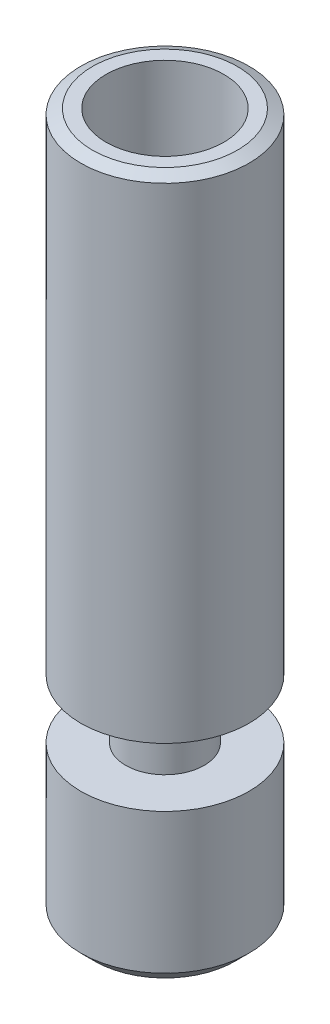
SolidWorks part; units mm, degrees
material "1060 Alloy"
ref_plane "Front Plane" through (0, 0, 0) normal (0, 0, 1) x (1, 0, 0)
ref_plane "Top Plane" through (0, 0, 0) normal (0, 1, 0) x (1, 0, 0)
ref_plane "Right Plane" through (0, 0, 0) normal (1, 0, 0) x (0, 0, -1)
ref_plane "Plane1" through (0, 0, 0) normal (0, 0, -1) x (-1, 0, 0)
sketch "Sketch1" plane through (0, 0, 0) normal (0, 0, -1) x (-1, 0, 0)
  line L0 (-2.5, -0.5) -> (-1, -0.5)
  line L1 (-1, -0.5) -> (-1, 15.3)
  line L2 (-1, 15.3) -> (-2.1, 16.4)
  line L3 (-2.1, 16.4) -> (-2.1, 24.5963)
  line L4 (-2.1, 24.5963) -> (-2.5868, 24.5963)
  line L5 (-3, 24.4) -> (-2.5868, 24.5963)
  line L6 (-3, 24.4) -> (-3, 16.9)
  line L8 (-3, 16.9) -> (-3, 7.1)
  line L9 (-3, 7.1) -> (-1.4, 7.1)
  line L10 (-1.4, 7.1) -> (-1.4, 5)
  line L11 (-1.4, 5) -> (-3, 5)
  line L12 (-3, 5) -> (-3, 0)
  line L13 (-3, 0) -> (-2.5, -0.5)
  line L14 (0, -0.5) -> (0, 24.6) construction
  dimension "D1" = 25.1
  dimension "D2" = 15.8
  dimension "D3" = 7.5
  dimension "D4" = 9.8
  dimension "D5" = 5
  dimension "D6" = 2.1
  dimension "D7" = 8.1963
revolve "Revolve1" add sketch "Sketch1" angle 360 about L14
